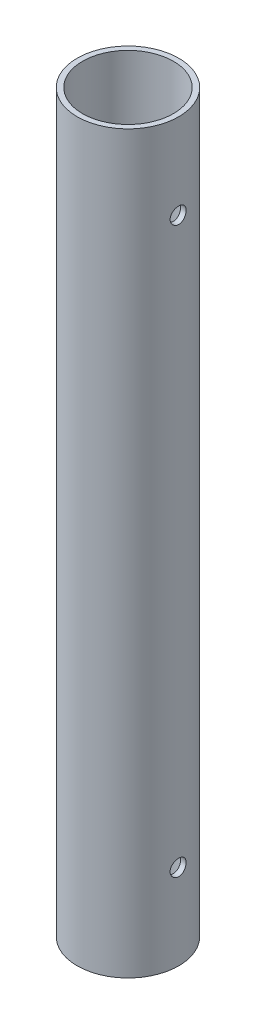
SolidWorks part; units mm, degrees
material "PVC Rigid"
ref_plane "Front" through (0, 0, 0) normal (0, 0, 1) x (1, 0, 0)
ref_plane "Top" through (0, 0, 0) normal (0, 1, 0) x (1, 0, 0)
ref_plane "Right" through (0, 0, 0) normal (1, 0, 0) x (0, 0, -1)
sketch "Sketch2" plane through (0, 0, 0) normal (0, 1, 0) x (1, 0, 0)
  circle A0 centre (0, 0) radius 60.49
  circle A1 centre (0, 0) radius 54.14
  dimension "D1" = 120.98
  dimension "D2" = 6.35
extrude "Boss-Extrude1" add sketch "Sketch2" along normal blind 876.3
sketch "Sketch3" plane through (0, 0, 0) normal (1, 0, 0) x (0, 0, -1)
  line L0 (60.49, 876.3) -> (-60.49, 876.3) construction
  line L1 (-60.49, 0) -> (60.49, 0) construction
  circle A0 centre (0, 101.6) radius 9.525
  circle A1 centre (0, 774.7) radius 9.525
  dimension "D1" = 19.05
  dimension "D2" = 101.6
  dimension "D3" = 101.6
extrude "Cut-Extrude1" cut sketch "Sketch3" against normal mid plane 876.3
